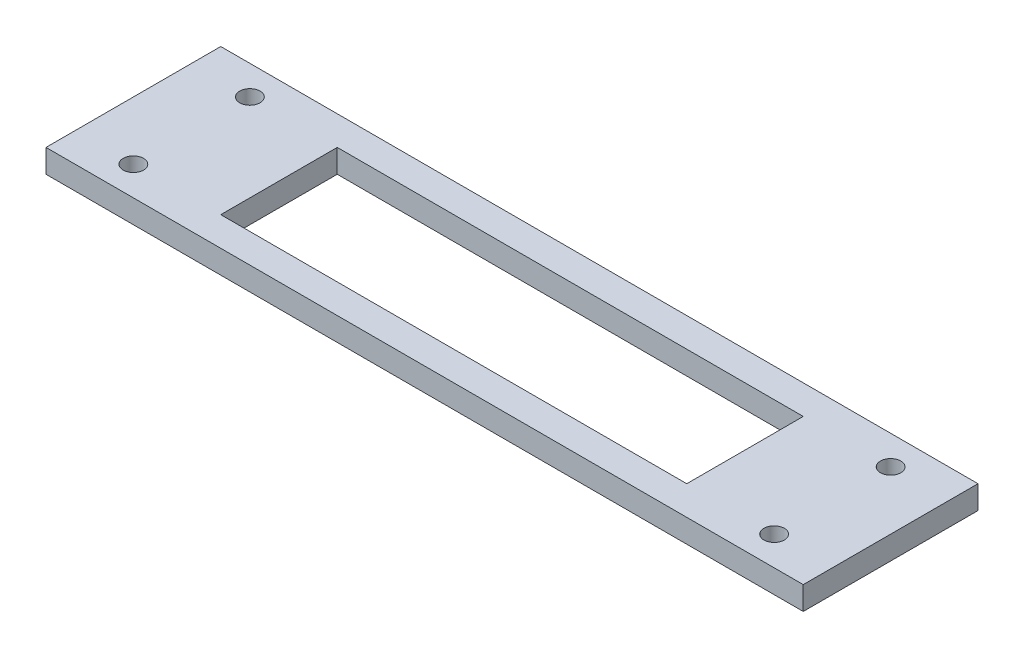
SolidWorks part; units mm, degrees
ref_plane "Front Plane" through (0, 0, 0) normal (0, 0, 1) x (1, 0, 0)
ref_plane "Top Plane" through (0, 0, 0) normal (0, 1, 0) x (1, 0, 0)
ref_plane "Right Plane" through (0, 0, 0) normal (1, 0, 0) x (0, 0, -1)
sketch "Sketch1" plane through (0, 0, 0) normal (0, 1, 0) x (1, 0, 0)
  line L0 (120, 14.79) -> (120, 5)
  line L1 (0, 0) -> (130, 0)
  line L2 (0, 0) -> (0, 30)
  line L3 (0, 30) -> (130, 30)
  line L4 (130, 0) -> (130, 30)
  line L5 (120, 14.5419) -> (120, 25)
  line L6 (65, 0) -> (65, 30)
  line L7 (0, 15) -> (130, 15)
  circle A2 centre (120, 25) radius 1.75
  circle A3 centre (120, 5) radius 1.75
  circle A4 centre (10, 5) radius 1.75
  circle A5 centre (10, 25) radius 1.75
  dimension "D5" = 10
  dimension "D10" = 3.5
  dimension "D11" = 3.5
  dimension "D3" = 10
  dimension "D4" = 10
  dimension "D1" = 130
  dimension "D2" = 30
extrude "Boss-Extrude1" add sketch "Sketch1" along normal blind 4
sketch "Sketch2" plane through (0, 4, 0) normal (0, 1, 0) x (1, 0, 0)
  line L0 (0, 30) -> (130, 30) construction
  line L1 (25, 25) -> (105, 25)
  line L2 (25, 25) -> (25, 5)
  line L3 (25, 5) -> (105, 5)
  line L4 (105, 25) -> (105, 5)
  line L5 (0, 0) -> (130, 0) construction
  line L6 (0, 0) -> (0, 30) construction
  line L7 (130, 0) -> (130, 30) construction
  dimension "D1" = 5
  dimension "D2" = 5
  dimension "D3" = 25
  dimension "D4" = 25
extrude "Cut-Extrude1" cut sketch "Sketch2" against normal through all
